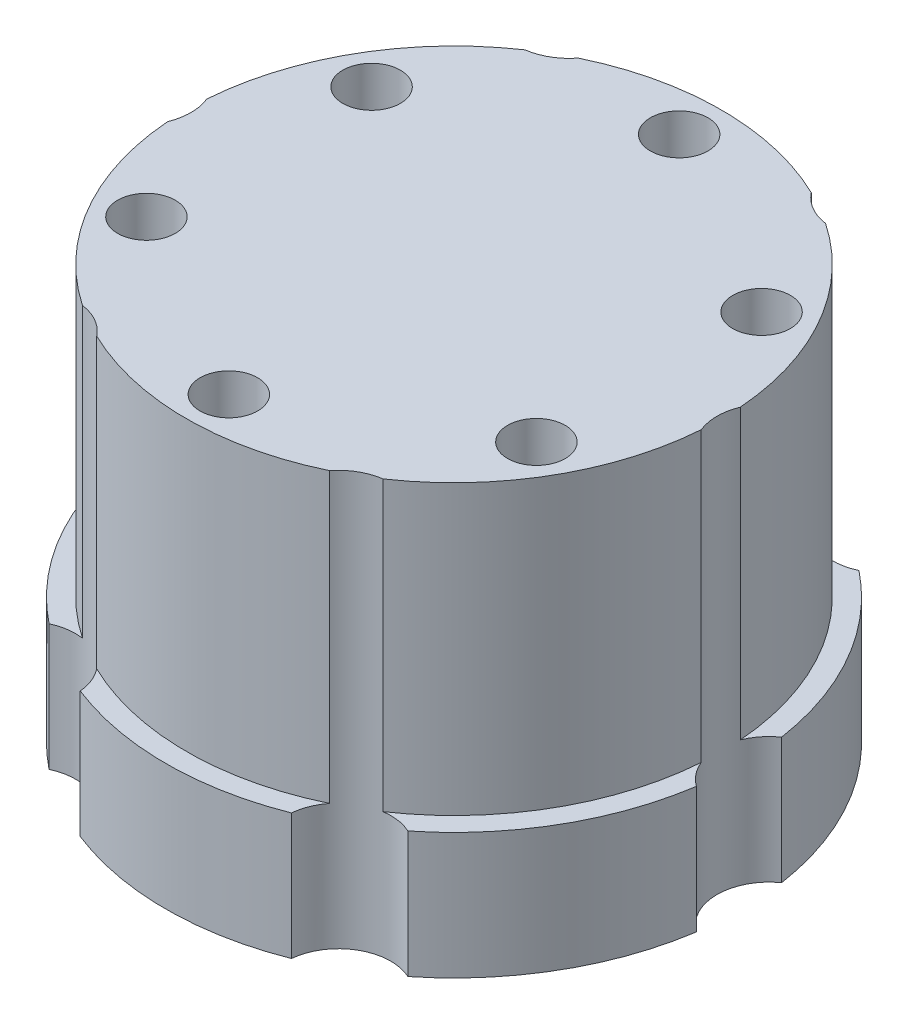
SolidWorks part; units mm, degrees
material "ABS"
ref_plane "前视基准面" through (0, 0, 0) normal (0, 0, 1) x (1, 0, 0)
ref_plane "上视基准面" through (0, 0, 0) normal (0, 1, 0) x (1, 0, 0)
ref_plane "右视基准面" through (0, 0, 0) normal (1, 0, 0) x (0, 0, -1)
other "Configuration Table"
sketch "草图1" plane through (0, 0, 0) normal (0, 1, 0) x (1, 0, 0)
  circle A0 centre (0, 0) radius 16
  dimension "D1" = 32
extrude "凸台-拉伸1" add sketch "草图1" along normal blind 7
sketch "草图2" plane through (0, 7, 0) normal (0, 1, 0) x (1, 0, 0)
  circle A0 centre (0, 0) radius 14.85
  dimension "D1" = 29.7
extrude "凸台-拉伸2" add sketch "草图2" along normal blind 16
sketch "草图3" plane through (0, 23, 0) normal (0, 1, 0) x (1, 0, 0)
  circle A0 centre (0, 0) radius 12.5 construction
  circle A1 centre (0, 12.5) radius 1.6
  circle A2 centre (10.8253, 6.25) radius 1.6
  circle A3 centre (10.8253, -6.25) radius 1.6
  circle A4 centre (0, -12.5) radius 1.6
  circle A5 centre (-10.8253, -6.25) radius 1.6
  circle A6 centre (-10.8253, 6.25) radius 1.6
  dimension "D1" = 25
  dimension "D2" = 3.2
extrude "切除-拉伸1" cut sketch "草图3" against normal through all
sketch "草图4" plane through (0, 0, 0) normal (0, -1, 0) x (1, 0, 0)
  line L0 (17.5, 0) -> (0, 0) construction
  line L1 (0, 0) -> (8.75, 15.1554) construction
  circle A0 centre (0, 0) radius 17.5 construction
  circle A1 centre (8.75, 15.1554) radius 2.9
  circle A2 centre (17.5, 0) radius 2.9
  circle A3 centre (8.75, -15.1554) radius 2.9
  circle A4 centre (-8.75, -15.1554) radius 2.9
  circle A5 centre (-17.5, 0) radius 2.9
  circle A6 centre (-8.75, 15.1554) radius 2.9
  dimension "D1" = 35
  dimension "D3" = 5.8
  dimension "D2" = 60
  dimension "D4" = 6
extrude "切除-拉伸2" cut sketch "草图4" against normal through all
